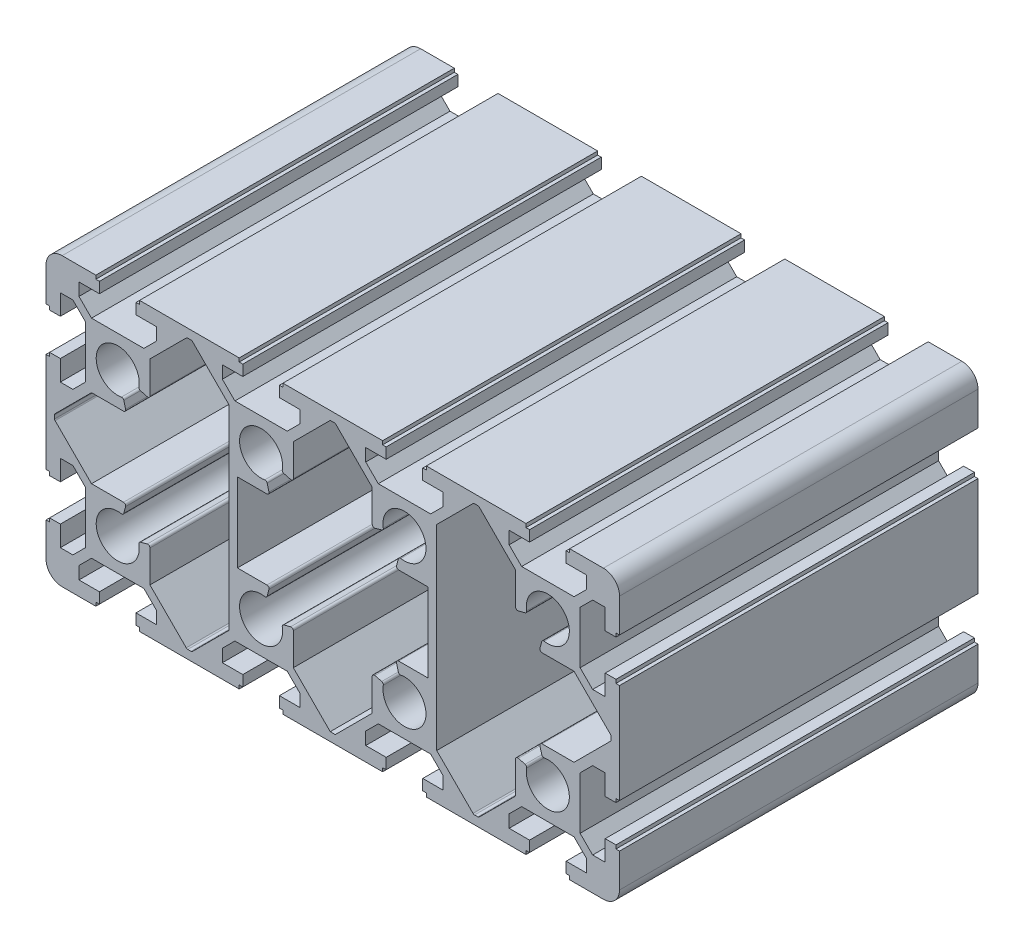
SolidWorks part; units mm, degrees
ref_plane "前视基准面" through (0, 0, 0) normal (0, 0, 1) x (1, 0, 0)
ref_plane "上视基准面" through (0, 0, 0) normal (0, 1, 0) x (1, 0, 0)
ref_plane "右视基准面" through (0, 0, 0) normal (1, 0, 0) x (0, 0, -1)
sketch "草图1" plane through (0, 0, 0) normal (0, 0, 1) x (1, 0, 0)
  line L0 (76.7284, -8.443) -> (73.2255, -8.443)
  line L1 (76.7284, -14.143) -> (76.7284, -8.443)
  line L2 (73.2255, -8.443) -> (69.7284, -11.94)
  line L3 (79.7284, -14.143) -> (76.7284, -14.143)
  line L4 (69.7284, -26.5459) -> (69.7284, -11.94)
  line L5 (79.7284, -14.143) -> (79.7284, -13.143)
  line L6 (73.2255, -30.043) -> (69.7284, -26.5459)
  line L7 (80.7284, -13.143) -> (79.7284, -13.143)
  line L8 (76.7284, -30.043) -> (73.2255, -30.043)
  line L9 (80.7284, -13.143) -> (80.7284, 14.657)
  line L10 (76.7284, -30.043) -> (76.7284, -24.343)
  line L11 (80.7284, 14.657) -> (79.7284, 14.657)
  line L12 (79.7284, -24.343) -> (76.7284, -24.343)
  line L13 (79.7284, 15.657) -> (79.7284, 14.657)
  line L14 (79.7284, -25.343) -> (79.7284, -24.343)
  line L15 (79.7284, 15.657) -> (76.7284, 15.657)
  line L16 (80.7284, -25.343) -> (79.7284, -25.343)
  line L17 (76.7284, 15.657) -> (76.7284, 9.957)
  line L18 (80.7284, -34.743) -> (80.7284, -25.343)
  line L19 (76.7284, 9.957) -> (73.2255, 9.957)
  line L20 (73.2255, 9.957) -> (69.7284, 13.4541)
  line L21 (76.2284, -39.243) -> (66.8284, -39.243)
  line L22 (69.7284, 28.06) -> (69.7284, 13.4541)
  line L23 (66.8284, -39.243) -> (66.8284, -38.243)
  line L24 (73.2255, 31.557) -> (69.7284, 28.06)
  line L25 (65.8284, -38.243) -> (66.8284, -38.243)
  line L26 (76.7284, 31.557) -> (73.2255, 31.557)
  line L27 (65.8284, -38.243) -> (65.8284, -35.243)
  line L28 (76.7284, 31.557) -> (76.7284, 25.857)
  line L29 (65.8284, -35.243) -> (71.5284, -35.243)
  line L30 (79.7284, 25.857) -> (76.7284, 25.857)
  line L31 (71.5284, -35.243) -> (71.5284, -31.74)
  line L32 (79.7284, 26.857) -> (79.7284, 25.857)
  line L33 (71.5284, -31.74) -> (68.0314, -28.243)
  line L34 (80.7284, 26.857) -> (79.7284, 26.857)
  line L35 (53.4255, -28.243) -> (68.0314, -28.243)
  line L36 (80.7284, 36.257) -> (80.7284, 26.857)
  line L37 (49.9284, -31.74) -> (53.4255, -28.243)
  line L38 (49.9284, -35.243) -> (49.9284, -31.74)
  line L39 (76.2284, 40.757) -> (66.8284, 40.757)
  line L40 (49.9284, -35.243) -> (55.6284, -35.243)
  line L41 (66.8284, 40.757) -> (66.8284, 39.757)
  line L42 (55.6284, -38.243) -> (55.6284, -35.243)
  line L43 (65.8284, 39.757) -> (66.8284, 39.757)
  line L44 (54.6284, -38.243) -> (55.6284, -38.243)
  line L45 (65.8284, 39.757) -> (65.8284, 36.757)
  line L46 (54.6284, -39.243) -> (54.6284, -38.243)
  line L47 (65.8284, 36.757) -> (71.5284, 36.757)
  line L48 (54.6284, -39.243) -> (26.8284, -39.243)
  line L49 (71.5284, 36.757) -> (71.5284, 33.2541)
  line L50 (26.8284, -39.243) -> (26.8284, -38.243)
  line L51 (71.5284, 33.2541) -> (68.0314, 29.757)
  line L52 (25.8284, -38.243) -> (26.8284, -38.243)
  line L53 (53.4255, 29.757) -> (68.0314, 29.757)
  line L54 (25.8284, -38.243) -> (25.8284, -35.243)
  line L55 (49.9284, 33.2541) -> (53.4255, 29.757)
  line L56 (25.8284, -35.243) -> (31.5284, -35.243)
  line L57 (49.9284, 36.757) -> (49.9284, 33.2541)
  line L58 (31.5284, -35.243) -> (31.5284, -31.74)
  line L59 (49.9284, 36.757) -> (55.6284, 36.757)
  line L60 (31.5284, -31.74) -> (28.0314, -28.243)
  line L61 (55.6284, 39.757) -> (55.6284, 36.757)
  line L62 (13.4255, -28.243) -> (28.0314, -28.243)
  line L63 (54.6284, 39.757) -> (55.6284, 39.757)
  line L64 (9.9284, -31.74) -> (13.4255, -28.243)
  line L65 (54.6284, 40.757) -> (54.6284, 39.757)
  line L66 (9.9284, -35.243) -> (9.9284, -31.74)
  line L67 (26.8284, 40.757) -> (54.6284, 40.757)
  line L68 (9.9284, -35.243) -> (15.6284, -35.243)
  line L69 (26.8284, 40.757) -> (26.8284, 39.757)
  line L70 (15.6284, -38.243) -> (15.6284, -35.243)
  line L71 (25.8284, 39.757) -> (26.8284, 39.757)
  line L72 (14.6284, -38.243) -> (15.6284, -38.243)
  line L73 (25.8284, 39.757) -> (25.8284, 36.757)
  line L74 (14.6284, -39.243) -> (14.6284, -38.243)
  line L75 (25.8284, 36.757) -> (31.5284, 36.757)
  line L76 (-13.1716, -39.243) -> (14.6284, -39.243)
  line L77 (31.5284, 36.757) -> (31.5284, 33.2541)
  line L78 (-13.1716, -39.243) -> (-13.1716, -38.243)
  line L79 (31.5284, 33.2541) -> (28.0314, 29.757)
  line L80 (-14.1716, -38.243) -> (-13.1716, -38.243)
  line L81 (13.4255, 29.757) -> (28.0314, 29.757)
  line L82 (-14.1716, -38.243) -> (-14.1716, -35.243)
  line L83 (9.9284, 33.2541) -> (13.4255, 29.757)
  line L84 (-14.1716, -35.243) -> (-8.4716, -35.243)
  line L85 (9.9284, 36.757) -> (9.9284, 33.2541)
  line L86 (-8.4716, -35.243) -> (-8.4716, -31.74)
  line L87 (9.9284, 36.757) -> (15.6284, 36.757)
  line L88 (-8.4716, -31.74) -> (-11.9686, -28.243)
  line L89 (15.6284, 39.757) -> (15.6284, 36.757)
  line L90 (-26.5745, -28.243) -> (-11.9686, -28.243)
  line L91 (14.6284, 39.757) -> (15.6284, 39.757)
  line L92 (-30.0716, -31.74) -> (-26.5745, -28.243)
  line L93 (14.6284, 40.757) -> (14.6284, 39.757)
  line L94 (-30.0716, -35.243) -> (-30.0716, -31.74)
  line L95 (14.6284, 40.757) -> (-13.1716, 40.757)
  line L96 (-30.0716, -35.243) -> (-24.3716, -35.243)
  line L97 (-13.1716, 40.757) -> (-13.1716, 39.757)
  line L98 (-24.3716, -38.243) -> (-24.3716, -35.243)
  line L99 (-14.1716, 39.757) -> (-13.1716, 39.757)
  line L100 (-25.3716, -38.243) -> (-24.3716, -38.243)
  line L101 (-14.1716, 39.757) -> (-14.1716, 36.757)
  line L102 (-25.3716, -39.243) -> (-25.3716, -38.243)
  line L103 (-14.1716, 36.757) -> (-8.4716, 36.757)
  line L104 (-25.3716, -39.243) -> (-53.1716, -39.243)
  line L105 (-8.4716, 36.757) -> (-8.4716, 33.2541)
  line L106 (-53.1716, -39.243) -> (-53.1716, -38.243)
  line L107 (-8.4716, 33.2541) -> (-11.9686, 29.757)
  line L108 (-54.1716, -38.243) -> (-53.1716, -38.243)
  line L109 (-26.5745, 29.757) -> (-11.9686, 29.757)
  line L110 (-54.1716, -38.243) -> (-54.1716, -35.243)
  line L111 (-30.0716, 33.2541) -> (-26.5745, 29.757)
  line L112 (-54.1716, -35.243) -> (-48.4716, -35.243)
  line L113 (-30.0716, 36.757) -> (-30.0716, 33.2541)
  line L114 (-48.4716, -35.243) -> (-48.4716, -31.74)
  line L115 (-30.0716, 36.757) -> (-24.3716, 36.757)
  line L116 (-48.4716, -31.74) -> (-51.9686, -28.243)
  line L117 (-24.3716, 39.757) -> (-24.3716, 36.757)
  line L118 (-66.5745, -28.243) -> (-51.9686, -28.243)
  line L119 (-25.3716, 39.757) -> (-24.3716, 39.757)
  line L120 (-70.0716, -31.74) -> (-66.5745, -28.243)
  line L121 (-25.3716, 40.757) -> (-25.3716, 39.757)
  line L122 (-70.0716, -35.243) -> (-70.0716, -31.74)
  line L123 (-53.1716, 40.757) -> (-25.3716, 40.757)
  line L124 (-70.0716, -35.243) -> (-64.3716, -35.243)
  line L125 (-53.1716, 40.757) -> (-53.1716, 39.757)
  line L126 (-64.3716, -38.243) -> (-64.3716, -35.243)
  line L127 (-54.1716, 39.757) -> (-53.1716, 39.757)
  line L128 (-65.3716, -38.243) -> (-64.3716, -38.243)
  line L129 (-54.1716, 39.757) -> (-54.1716, 36.757)
  line L130 (-65.3716, -39.243) -> (-65.3716, -38.243)
  line L131 (-54.1716, 36.757) -> (-48.4716, 36.757)
  line L132 (-74.7716, -39.243) -> (-65.3716, -39.243)
  line L133 (-48.4716, 36.757) -> (-48.4716, 33.2541)
  line L134 (-48.4716, 33.2541) -> (-51.9686, 29.757)
  line L135 (-79.2716, -34.743) -> (-79.2716, -25.343)
  line L136 (-66.5745, 29.757) -> (-51.9686, 29.757)
  line L137 (-79.2716, -25.343) -> (-78.2716, -25.343)
  line L138 (-70.0716, 33.2541) -> (-66.5745, 29.757)
  line L139 (-78.2716, -25.343) -> (-78.2716, -24.343)
  line L140 (-70.0716, 36.757) -> (-70.0716, 33.2541)
  line L141 (-78.2716, -24.343) -> (-75.2716, -24.343)
  line L142 (-70.0716, 36.757) -> (-64.3716, 36.757)
  line L143 (-75.2716, -30.043) -> (-75.2716, -24.343)
  line L144 (-64.3716, 39.757) -> (-64.3716, 36.757)
  line L145 (-75.2716, -30.043) -> (-71.7686, -30.043)
  line L146 (-65.3716, 39.757) -> (-64.3716, 39.757)
  line L147 (-71.7686, -30.043) -> (-68.2716, -26.5459)
  line L148 (-65.3716, 40.757) -> (-65.3716, 39.757)
  line L149 (-68.2716, -26.5459) -> (-68.2716, -11.94)
  line L150 (-74.7716, 40.757) -> (-65.3716, 40.757)
  line L151 (-71.7686, -8.443) -> (-68.2716, -11.94)
  line L152 (-75.2716, -8.443) -> (-71.7686, -8.443)
  line L153 (-79.2716, 26.857) -> (-79.2716, 36.257)
  line L154 (-75.2716, -14.143) -> (-75.2716, -8.443)
  line L155 (-79.2716, 26.857) -> (-78.2716, 26.857)
  line L156 (-78.2716, -14.143) -> (-75.2716, -14.143)
  line L157 (-78.2716, 26.857) -> (-78.2716, 25.857)
  line L158 (-78.2716, -14.143) -> (-78.2716, -13.143)
  line L159 (-78.2716, 25.857) -> (-75.2716, 25.857)
  line L160 (-79.2716, -13.143) -> (-78.2716, -13.143)
  line L161 (-75.2716, 31.557) -> (-75.2716, 25.857)
  line L162 (-79.2716, 14.657) -> (-79.2716, -13.143)
  line L163 (-75.2716, 31.557) -> (-71.7686, 31.557)
  line L164 (-79.2716, 14.657) -> (-78.2716, 14.657)
  line L165 (-71.7686, 31.557) -> (-68.2716, 28.06)
  line L166 (-78.2716, 15.657) -> (-78.2716, 14.657)
  line L167 (-68.2716, 28.06) -> (-68.2716, 13.4541)
  line L168 (-78.2716, 15.657) -> (-75.2716, 15.657)
  line L169 (-71.7686, 9.957) -> (-68.2716, 13.4541)
  line L170 (-75.2716, 15.657) -> (-75.2716, 9.957)
  line L171 (-75.2716, 9.957) -> (-71.7686, 9.957)
  line L172 (-76.8716, 0.2612) -> (-76.8716, 1.2528)
  line L173 (-66.5745, -10.243) -> (-76.7251, -0.0924)
  line L174 (-76.7251, 1.6064) -> (-66.5745, 11.757)
  line L175 (-57.642, -10.243) -> (-66.5745, -10.243)
  line L176 (-66.5745, 11.757) -> (-57.642, 11.757)
  line L177 (-57.5705, -12.8943) -> (-57.0624, -10.9983)
  line L178 (-57.0624, 12.5123) -> (-57.5705, 14.4083)
  line L179 (-51.0269, -17.0338) -> (-52.9229, -17.5419)
  line L180 (-52.9229, 19.0559) -> (-51.0269, 18.5478)
  line L181 (-50.2716, -26.5459) -> (-50.2716, -17.6134)
  line L182 (-50.2716, 19.1274) -> (-50.2716, 28.06)
  line L183 (-40.1503, -36.6673) -> (-50.2716, -26.5459)
  line L184 (-50.2716, 28.06) -> (-40.1503, 38.1813)
  line L185 (-38.8172, -36.843) -> (-39.726, -36.843)
  line L186 (-39.726, 38.357) -> (-38.8172, 38.357)
  line L187 (-28.2716, -26.5459) -> (-38.3929, -36.6673)
  line L188 (-38.3929, 38.1813) -> (-28.2716, 28.06)
  line L189 (-28.2716, 28.06) -> (-28.2716, -26.5459)
  line L190 (-10.2716, -26.5459) -> (-10.2716, -17.6134)
  line L191 (-11.0269, -17.0338) -> (-12.9229, -17.5419)
  line L192 (0.0255, -36.843) -> (-10.2716, -26.5459)
  line L193 (1.4314, -36.843) -> (0.0255, -36.843)
  line L194 (11.7284, -26.5459) -> (1.4314, -36.843)
  line L195 (11.7284, -26.5459) -> (11.7284, -17.6134)
  line L196 (-17.5705, -12.8943) -> (-17.0624, -10.9983)
  line L197 (12.4837, -17.0338) -> (14.3797, -17.5419)
  line L198 (-17.642, -10.243) -> (-25.8716, -10.243)
  line L199 (-25.8716, -10.243) -> (-25.8716, 11.757)
  line L200 (-25.8716, 11.757) -> (-17.642, 11.757)
  line L201 (19.0273, -12.8943) -> (18.5192, -10.9983)
  line L202 (-17.0624, 12.5123) -> (-17.5705, 14.4083)
  line L203 (19.0988, -10.243) -> (27.3284, -10.243)
  line L204 (27.3284, 11.757) -> (27.3284, -10.243)
  line L205 (27.3284, 11.757) -> (19.0988, 11.757)
  line L206 (-12.9229, 19.0559) -> (-11.0269, 18.5478)
  line L207 (18.5192, 12.5123) -> (19.0273, 14.4083)
  line L208 (-10.2716, 19.1274) -> (-10.2716, 28.06)
  line L209 (-10.2716, 28.06) -> (0.0255, 38.357)
  line L210 (0.0255, 38.357) -> (1.4314, 38.357)
  line L211 (1.4314, 38.357) -> (11.7284, 28.06)
  line L212 (14.3797, 19.0559) -> (12.4837, 18.5478)
  line L213 (11.7284, 19.1274) -> (11.7284, 28.06)
  line L214 (58.5192, 12.5123) -> (59.0273, 14.4083)
  line L215 (54.3797, 19.0559) -> (52.4837, 18.5478)
  line L216 (68.0314, 11.757) -> (59.0988, 11.757)
  line L217 (68.0314, 11.757) -> (78.182, 1.6064)
  line L218 (51.7284, 19.1274) -> (51.7284, 28.06)
  line L219 (41.6071, 38.1813) -> (51.7284, 28.06)
  line L220 (78.3284, 1.2528) -> (78.3284, 0.2612)
  line L221 (40.274, 38.357) -> (41.1828, 38.357)
  line L222 (78.182, -0.0924) -> (68.0314, -10.243)
  line L223 (59.0988, -10.243) -> (68.0314, -10.243)
  line L224 (29.7284, 28.06) -> (39.8497, 38.1813)
  line L225 (29.7284, -26.5459) -> (29.7284, 28.06)
  line L226 (59.0273, -12.8943) -> (58.5192, -10.9983)
  line L227 (39.8497, -36.6673) -> (29.7284, -26.5459)
  line L228 (41.1828, -36.843) -> (40.274, -36.843)
  line L229 (52.4837, -17.0338) -> (54.3797, -17.5419)
  line L230 (51.7284, -26.5459) -> (41.6071, -36.6673)
  line L231 (51.7284, -26.5459) -> (51.7284, -17.6134)
  arc A0 (76.2284, -39.243) -> (80.7284, -34.743) centre (76.2284, -34.743) ccw
  arc A1 (80.7284, 36.257) -> (76.2284, 40.757) centre (76.2284, 36.257) ccw
  arc A2 (-79.2716, -34.743) -> (-74.7716, -39.243) centre (-74.7716, -34.743) ccw
  arc A3 (-74.7716, 40.757) -> (-79.2716, 36.257) centre (-74.7716, 36.257) ccw
  arc A4 (-76.8716, 0.2612) -> (-76.7251, -0.0924) centre (-76.3716, 0.2612) ccw
  arc A5 (-76.7251, 1.6064) -> (-76.8716, 1.2528) centre (-76.3716, 1.2528) ccw
  arc A6 (-57.0624, -10.9983) -> (-57.642, -10.243) centre (-57.642, -10.843) ccw
  arc A7 (-57.642, 11.757) -> (-57.0624, 12.5123) centre (-57.642, 12.357) ccw
  arc A8 (-58.252, -13.3303) -> (-57.5705, -12.8943) centre (-58.15, -12.739) ccw
  arc A9 (-57.5705, 14.4083) -> (-58.252, 14.8443) centre (-58.15, 14.253) ccw
  arc A10 (-58.252, -13.3303) -> (-53.3589, -18.2234) centre (-59.2716, -19.243) ccw
  arc A11 (-53.3589, 19.7374) -> (-58.252, 14.8443) centre (-59.2716, 20.757) ccw
  arc A12 (-52.9229, -17.5419) -> (-53.3589, -18.2234) centre (-52.7676, -18.1214) ccw
  arc A13 (-53.3589, 19.7374) -> (-52.9229, 19.0559) centre (-52.7676, 19.6354) ccw
  arc A14 (-50.2716, -17.6134) -> (-51.0269, -17.0338) centre (-50.8716, -17.6134) ccw
  arc A15 (-51.0269, 18.5478) -> (-50.2716, 19.1274) centre (-50.8716, 19.1274) ccw
  arc A16 (-40.1503, -36.6673) -> (-39.726, -36.843) centre (-39.726, -36.243) ccw
  arc A17 (-39.726, 38.357) -> (-40.1503, 38.1813) centre (-39.726, 37.757) ccw
  arc A18 (-38.8172, -36.843) -> (-38.3929, -36.6673) centre (-38.8172, -36.243) ccw
  arc A19 (-38.3929, 38.1813) -> (-38.8172, 38.357) centre (-38.8172, 37.757) ccw
  arc A20 (-10.2716, -17.6134) -> (-11.0269, -17.0338) centre (-10.8716, -17.6134) ccw
  arc A21 (-12.9229, -17.5419) -> (-13.3589, -18.2234) centre (-12.7676, -18.1214) ccw
  arc A22 (-18.252, -13.3303) -> (-13.3589, -18.2234) centre (-19.2716, -19.243) ccw
  arc A23 (-18.252, -13.3303) -> (-17.5705, -12.8943) centre (-18.15, -12.739) ccw
  arc A24 (12.4837, -17.0338) -> (11.7284, -17.6134) centre (12.3284, -17.6134) ccw
  arc A25 (-17.0624, -10.9983) -> (-17.642, -10.243) centre (-17.642, -10.843) ccw
  arc A26 (14.8157, -18.2234) -> (14.3797, -17.5419) centre (14.2244, -18.1214) ccw
  arc A27 (14.8157, -18.2234) -> (19.7088, -13.3303) centre (20.7284, -19.243) ccw
  arc A28 (19.0273, -12.8943) -> (19.7088, -13.3303) centre (19.6068, -12.739) ccw
  arc A29 (-17.642, 11.757) -> (-17.0624, 12.5123) centre (-17.642, 12.357) ccw
  arc A30 (19.0988, -10.243) -> (18.5192, -10.9983) centre (19.0988, -10.843) ccw
  arc A31 (-17.5705, 14.4083) -> (-18.252, 14.8443) centre (-18.15, 14.253) ccw
  arc A32 (-13.3589, 19.7374) -> (-18.252, 14.8443) centre (-19.2716, 20.757) ccw
  arc A33 (-13.3589, 19.7374) -> (-12.9229, 19.0559) centre (-12.7676, 19.6354) ccw
  arc A34 (18.5192, 12.5123) -> (19.0988, 11.757) centre (19.0988, 12.357) ccw
  arc A35 (-11.0269, 18.5478) -> (-10.2716, 19.1274) centre (-10.8716, 19.1274) ccw
  arc A36 (19.7088, 14.8443) -> (19.0273, 14.4083) centre (19.6068, 14.253) ccw
  arc A37 (19.7088, 14.8443) -> (14.8157, 19.7374) centre (20.7284, 20.757) ccw
  arc A38 (14.3797, 19.0559) -> (14.8157, 19.7374) centre (14.2244, 19.6354) ccw
  arc A39 (11.7284, 19.1274) -> (12.4837, 18.5478) centre (12.3284, 19.1274) ccw
  arc A40 (59.7088, 14.8443) -> (59.0273, 14.4083) centre (59.6068, 14.253) ccw
  arc A41 (59.7088, 14.8443) -> (54.8157, 19.7374) centre (60.7284, 20.757) ccw
  arc A42 (54.3797, 19.0559) -> (54.8157, 19.7374) centre (54.2244, 19.6354) ccw
  arc A43 (58.5192, 12.5123) -> (59.0988, 11.757) centre (59.0988, 12.357) ccw
  arc A44 (51.7284, 19.1274) -> (52.4837, 18.5478) centre (52.3284, 19.1274) ccw
  arc A45 (78.3284, 1.2528) -> (78.182, 1.6064) centre (77.8284, 1.2528) ccw
  arc A46 (41.6071, 38.1813) -> (41.1828, 38.357) centre (41.1828, 37.757) ccw
  arc A47 (78.182, -0.0924) -> (78.3284, 0.2612) centre (77.8284, 0.2612) ccw
  arc A48 (40.274, 38.357) -> (39.8497, 38.1813) centre (40.274, 37.757) ccw
  arc A49 (59.0988, -10.243) -> (58.5192, -10.9983) centre (59.0988, -10.843) ccw
  arc A50 (59.0273, -12.8943) -> (59.7088, -13.3303) centre (59.6068, -12.739) ccw
  arc A51 (39.8497, -36.6673) -> (40.274, -36.843) centre (40.274, -36.243) ccw
  arc A52 (54.8157, -18.2234) -> (59.7088, -13.3303) centre (60.7284, -19.243) ccw
  arc A53 (54.8157, -18.2234) -> (54.3797, -17.5419) centre (54.2244, -18.1214) ccw
  arc A54 (41.1828, -36.843) -> (41.6071, -36.6673) centre (41.1828, -36.243) ccw
  arc A55 (52.4837, -17.0338) -> (51.7284, -17.6134) centre (52.3284, -17.6134) ccw
extrude "凸台-拉伸1" add sketch "草图1" along normal blind 100
